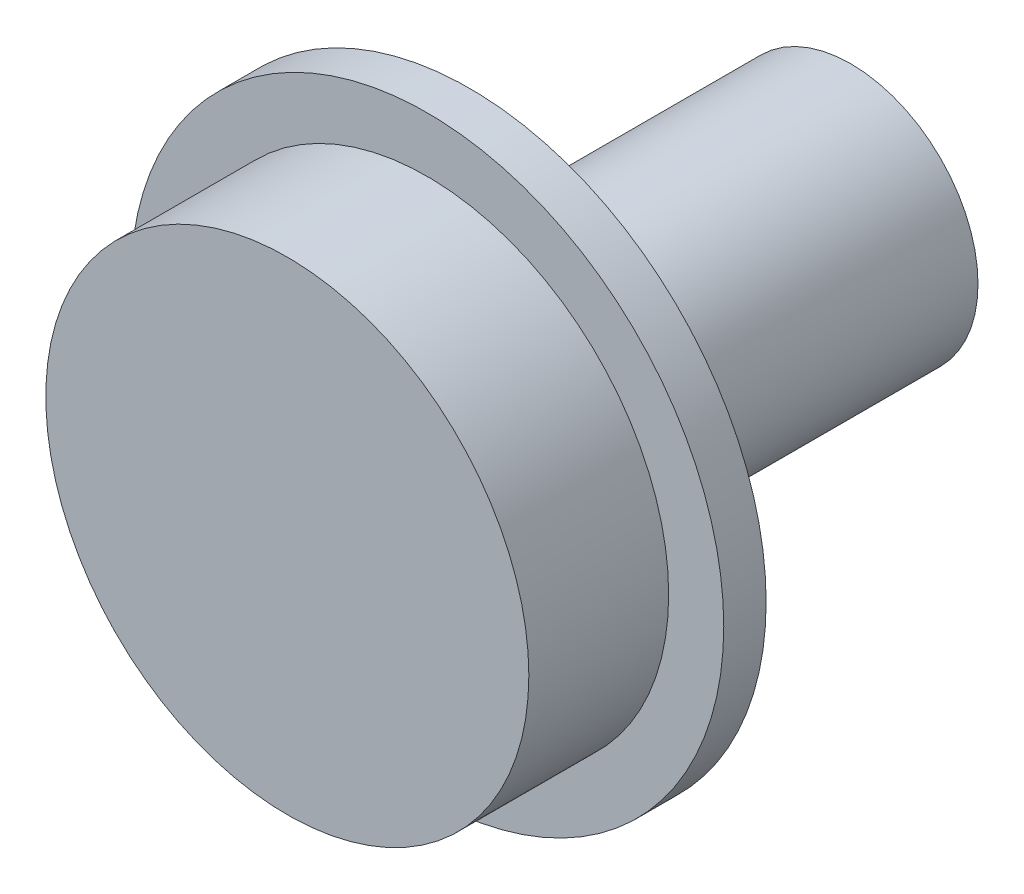
SolidWorks part; units mm, degrees
ref_plane "Front Plane" through (0, 0, 0) normal (0, 0, 1) x (1, 0, 0)
ref_plane "Top Plane" through (0, 0, 0) normal (0, 1, 0) x (1, 0, 0)
ref_plane "Right Plane" through (0, 0, 0) normal (1, 0, 0) x (0, 0, -1)
sketch "Low screw head profile" plane through (0, 0, 0) normal (0, 0, 1) x (1, 0, 0)
  circle A0 centre (0, 0) radius 2.85
extrude "Low screw head" add sketch "Low screw head profile" along normal blind 1.65 from offset 0.5
sketch "M3 shank, threads omitted profile" plane through (0, 0, 0) normal (0, 0, 1) x (1, 0, 0)
  circle A0 centre (0, 0) radius 1.5
extrude "M3 shank, threads omitted" add sketch "M3 shank, threads omitted profile" along normal blind 5 from offset 4.5
sketch "M3 washer envelope profile" plane through (0, 0, 0) normal (0, 0, 1) x (1, 0, 0)
  circle A0 centre (0, 0) radius 3.5
  circle A1 centre (0, 0) radius 1.7
extrude "M3 washer envelope" add sketch "M3 washer envelope profile" along normal blind 0.5
